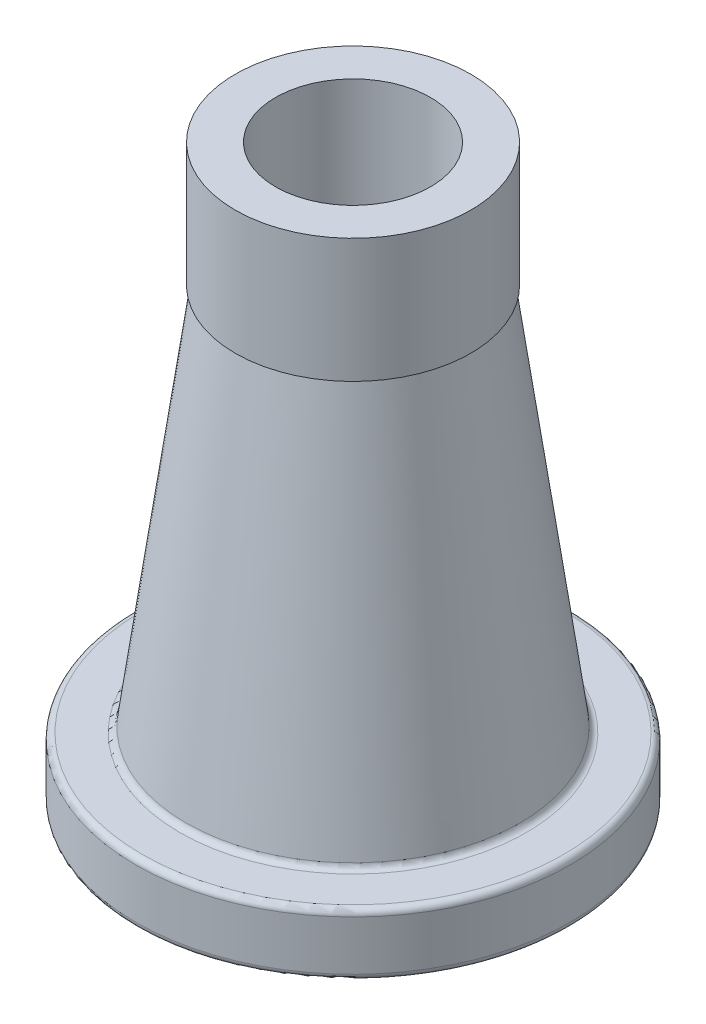
SolidWorks part; units mm, degrees
ref_plane "Front Plane" through (0, 0, 0) normal (0, 0, 1) x (1, 0, 0)
ref_plane "Top Plane" through (0, 0, 0) normal (0, 1, 0) x (1, 0, 0)
ref_plane "Right Plane" through (0, 0, 0) normal (1, 0, 0) x (0, 0, -1)
sketch "Sketch1" plane through (0, 0, 0) normal (0, 0, 1) x (1, 0, 0)
  line L0 (0, 0) -> (68, 0)
  line L1 (0, 0) -> (0, 185) construction
  line L2 (0, 3) -> (48, 3)
  line L3 (50, 1) -> (50, 0)
  line L4 (70, 2) -> (70, 18)
  line L5 (0, 185) -> (25, 185)
  line L6 (25, 185) -> (25, 145)
  line L7 (0, 185) -> (38, 185)
  line L8 (38, 185) -> (38, 145)
  line L9 (38, 145) -> (37.5731, 145)
  line L10 (25, 145) -> (44, 3)
  line L11 (0, 185) -> (0, 0)
  line L12 (68, 20) -> (55.8572, 20)
  line L14 (34.5, 74) -> (46.5, 75.6056) construction
  line L15 (37.0777, 144.4322) -> (46.5, 75.6056)
  line L16 (46.5, 75.6056) -> (53.8757, 21.7287)
  line L17 (25, 145) -> (0, 145)
  arc A0 (50, 1) -> (48, 3) centre (48, 1) ccw
  arc A1 (55.8572, 20) -> (53.8757, 21.7287) centre (55.8572, 22) cw
  arc A2 (37.0777, 144.4322) -> (37.5731, 145) centre (37.5731, 144.5) cw
  arc A3 (68, 0) -> (70, 2) centre (68, 2) ccw
  arc A4 (70, 18) -> (68, 20) centre (68, 18) ccw
  point P9 (50, 3)
  point P24 (37, 145)
  point P28 (70, 0)
  point P31 (70, 20)
  dimension "D4" = 2
  dimension "D12" = 90
  dimension "D14" = 2
  dimension "D15" = 0.5
  dimension "D16" = 2
  dimension "D1" = 3
  dimension "D2" = 50
  dimension "D3" = 70
  dimension "D5" = 20
  dimension "D6" = 185
  dimension "D7" = 25
  dimension "D8" = 40
  dimension "D9" = 38
  dimension "D10" = 1
  dimension "D11" = 44
  dimension "D13" = 12
revolve "Revolve1" add sketch "Sketch1" angle 360 about L11
